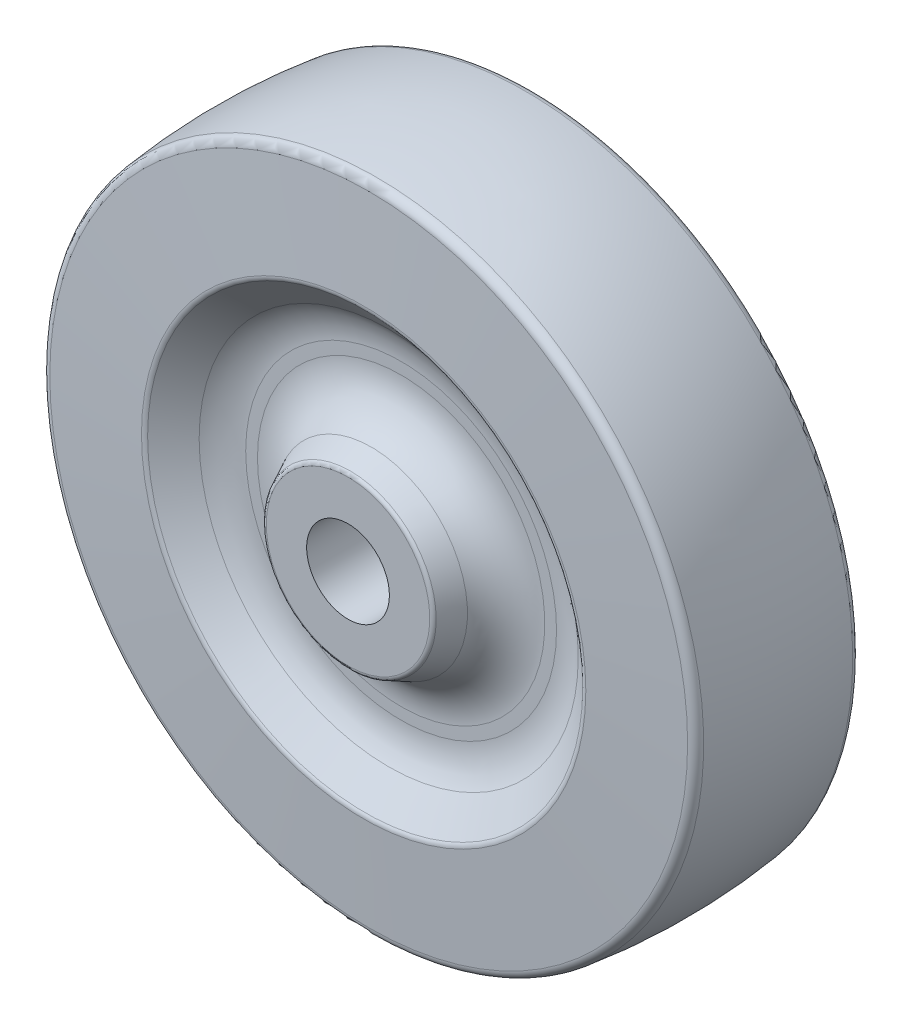
SolidWorks part; units mm, degrees
ref_plane "Front Plane" through (0, 0, 0) normal (0, 0, 1) x (1, 0, 0)
ref_plane "Top Plane" through (0, 0, 0) normal (0, 1, 0) x (1, 0, 0)
ref_plane "Right Plane" through (0, 0, 0) normal (1, 0, 0) x (0, 0, -1)
sketch "Sketch1" plane through (0, 0, 0) normal (1, 0, 0) x (0, 0, -1)
  line L0 (0, -38.1) -> (0, 38.1) construction
  line L1 (-11.8237, 0) -> (11.8237, 0) construction
  line L2 (-10.0457, 38.1) -> (10.0457, 38.1) construction
  point P0 (0, 3.175)
  point P3 (0, -3.175)
  point P4 (0, 0)
  point P8 (0, 0)
  point P11 (0, 38.1)
  point P14 (0, 4.7498)
  point P16 (0, -4.7498)
  point P17 (11.8237, 0)
  dimension "Wheel Diameter" = 76.2
  dimension "Hub Length" = 23.6474
  dimension "Wheel Width" = 20.0914
  dimension "For Axle Diameter" = 6.35
  dimension "D2" = 3.175
  dimension "Sleeve Bearing Diameter" = 9.4996
sketch "Sketch2" plane through (0, 0, 0) normal (1, 0, 0) x (0, 0, -1)
  line L6 (10.0457, 38.1) -> (0, 38.1) construction
  line L8 (0, 0) -> (0, 38.1) construction
  line L9 (0, -38.1) -> (0, 38.1) construction
  line L13 (5.7277, 20.066) -> (10.0457, 20.066) construction
  line L25 (5.7277, 12.7) -> (10.0457, 12.7) construction
  line L26 (-10.0457, 38.1) -> (0, 38.1) construction
  line L27 (10.0457, 25.212) -> (10.0457, 37.3738) construction
  line L28 (10.0457, 25.212) -> (5.7277, 20.066)
  line L29 (5.7277, 20.066) -> (5.7277, 12.7)
  line L30 (-11.8237, 0) -> (11.8237, 0) construction
  line L31 (11.8237, 9.7028) -> (5.7277, 12.7)
  line L33 (11.8237, 9.7028) -> (11.8237, 0)
  line L38 (-11.8237, 0) -> (11.8237, 0)
  line L39 (10.0457, 25.212) -> (9.4036, 37.4641)
  line L40 (-11.8237, 9.7028) -> (-11.8237, 0)
  line L41 (-11.8237, 9.7028) -> (-5.7277, 12.7)
  line L42 (-5.7277, 20.066) -> (-5.7277, 12.7)
  line L43 (-10.0457, 25.212) -> (-5.7277, 20.066)
  line L44 (-10.0457, 25.212) -> (-9.4036, 37.4641)
  arc A0 (0, 38.1) -> (10.0457, 37.3738) centre (0, -31.75) cw construction
  arc A1 (-9.4036, 37.4641) -> (9.4036, 37.4641) centre (0, -31.75) cw
  point P25 (0, 0)
  dimension "D3" = 12.7
  dimension "D4" = 9.7028
  dimension "D5" = 20.066
  dimension "D6" = 69.85
  dimension "D7" = 3
  dimension "D1" = 50
  dimension "D2" = 4.318
revolve "Revolve1" add sketch "Sketch2" angle 360 about L38
sketch "Sketch3" plane through (0, 0, 0) normal (1, 0, 0) x (0, 0, -1)
  line L12 (-11.8237, 0) -> (11.8237, 0) construction
  line L20 (11.8237, 0) -> (11.8237, 4.7498)
  line L21 (11.8237, 4.7498) -> (-11.8237, 4.7498)
  line L22 (-11.8237, 0) -> (-11.8237, 4.7498)
  line L25 (-11.8237, 0) -> (11.8237, 0)
  point P0 (0, 0)
revolve "Revolve2" add sketch "Sketch3" angle 360 about L25
sketch "Sketch6" plane through (0, 0, 0) normal (1, 0, 0) x (0, 0, -1)
  line L0 (0, -38.1) -> (0, 38.1) construction
  line L1 (-11.8237, 4.7498) -> (11.8237, 4.7498)
  line L5 (11.8237, 0) -> (-11.8237, 0)
  line L8 (-11.8237, 4.7498) -> (-11.8237, 0)
  line L9 (11.8237, 4.7498) -> (11.8237, 0)
  point P6 (0, 4.7498)
  point P11 (0, 0)
revolve "Cut-Revolve1" cut sketch "Sketch6" angle 360 about L1
sketch "Sketch4" plane through (0, 0, 0) normal (0, 0, 1) x (1, 0, 0)
  line L0 (0, -38.1) -> (0, 38.1) construction
  circle A0 centre (0, 0) radius 3.175
extrude "Cut-Extrude1" cut sketch "Sketch4" against normal through all both and the other way through all
fillet "Fillet1" radius 1.016 2 edges at (37.4641, 0, 9.4036) (37.4641, 0, -9.4036)
fillet "Fillet2" radius 6.096 4 edges at (20.066, 0, -5.7277) (12.7, 0, -5.7277) (12.7, 0, 5.7277) (20.066, 0, 5.7277)
fillet "Fillet3" radius 0.762 2 edges at (25.212, 0, 10.0457) (25.212, 0, -10.0457)
fillet "Fillet4" radius 0.508 2 edges at (9.7028, 0, -11.8237) (9.7028, 0, 11.8237)
sketch "Sketch8" plane through (0, 0, 0) normal (1, 0, 0) x (0, 0, -1)
  line L0 (0, -38.1) -> (0, 38.1) construction
  line L2 (-10.0457, 38.1) -> (10.0457, 38.1) construction
  line L3 (-11.8237, 0) -> (11.8237, 0) construction
  point P0 (10.0457, 33.02)
  point P5 (0, 0)
  point P6 (-10.0457, 33.02)
  point P12 (11.8237, -8.89)
  point P13 (-11.8237, -8.89)
  dimension "D1" = 5.08
  dimension "D2" = 8.89
sketch "Sketch9" plane through (0, 0, 0) normal (0, 0, 1) x (1, 0, 0)
  circle A0 centre (0, 0) radius 38.1 construction
  circle A1 centre (0, 0) radius 3.175 construction
sketch "Sketch10" plane through (0, 0, -11.8237) normal (0, 0, -1) x (-1, 0, 0)
  circle A0 centre (0, 0) radius 4.7498
  dimension "D1" = 9.4996
extrude "Cut-Extrude2" cut sketch "Sketch10" against normal through all
equation "\"D2@Sketch1\" = \"For Axle Diameter@Sketch1\" / 2"
